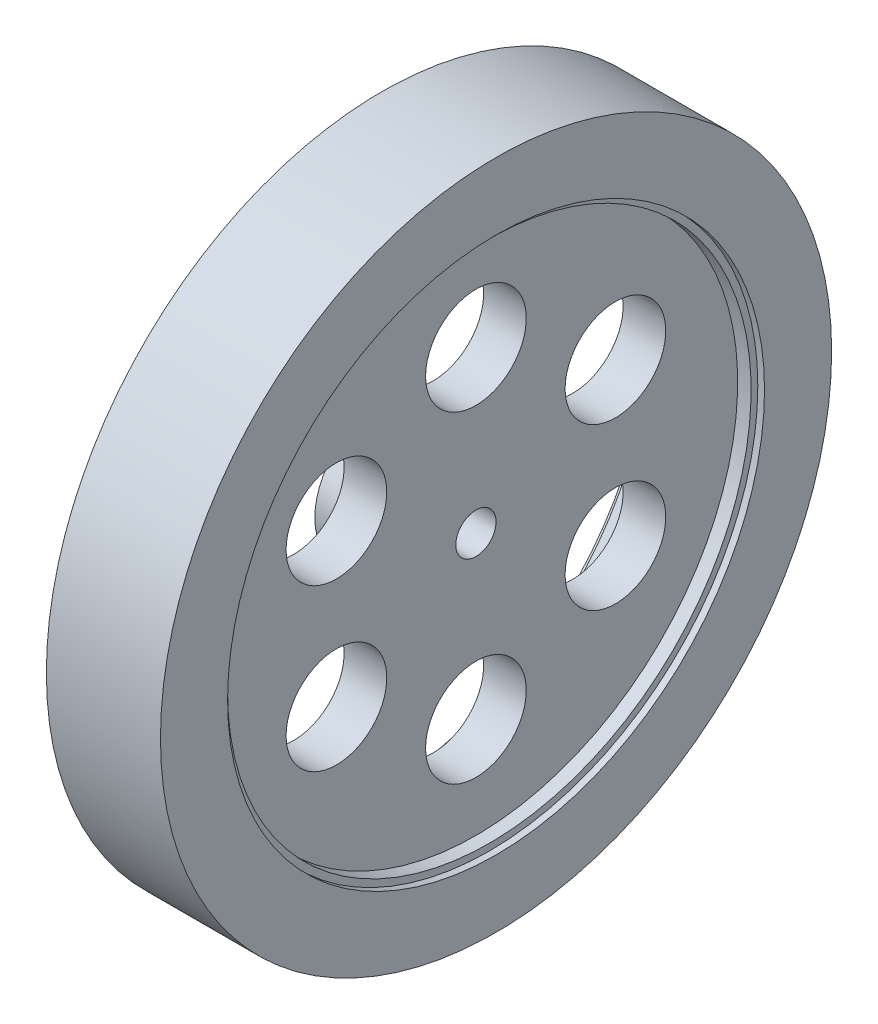
SolidWorks part; units mm, degrees
ref_plane "Front Plane" through (0, 0, 0) normal (0, 0, 1) x (1, 0, 0)
ref_plane "Top Plane" through (0, 0, 0) normal (0, 1, 0) x (1, 0, 0)
ref_plane "Right Plane" through (0, 0, 0) normal (1, 0, 0) x (0, 0, -1)
sketch "Sketch1" plane through (0, 0, 0) normal (0, 0, 1) x (1, 0, 0)
  line L0 (0, 1.5) -> (0, 19.5)
  line L1 (0, 19.5) -> (1, 19.5)
  line L2 (1, 19.5) -> (1, 20)
  line L4 (1.5, 20) -> (1.5, 25)
  line L5 (1.5, 25) -> (-7, 25)
  line L6 (-7, 25) -> (-7, 20)
  line L8 (-3.175, 19.5) -> (-3.175, 5)
  line L9 (-3.175, 0) -> (0, 0) construction
  line L10 (-7, 20) -> (-6.5, 20)
  line L11 (-6.5, 20) -> (-6.5, 19.5)
  line L12 (-6.5, 19.5) -> (-3.175, 19.5)
  line L13 (1, 20) -> (1.5, 20)
  line L14 (-3.175, 1.5) -> (-3.175, 0) construction
  line L15 (-3.175, 1.5) -> (-7, 1.5)
  line L17 (-3.175, 5) -> (-7, 5)
  line L18 (-7, 1.5) -> (-7, 5)
  line L19 (-3.175, 1.5) -> (0, 1.5)
  line L20 (0, 0) -> (0, 1.5) construction
  dimension "D1" = 8.5
  dimension "D2" = 5
  dimension "D3" = 3.175
  dimension "D4" = 0.5
  dimension "D5" = 1
  dimension "D6" = 25
  dimension "D7" = 1.5
  dimension "D8" = 3.5
revolve "Revolve1" add sketch "Sketch1" angle 360 about L9
sketch "Sketch2" plane through (-3.175, 0, 0) normal (-1, 0, 0) x (0, 0, 1)
  line L0 (0, 0) -> (0, 12) construction
  circle A0 centre (0, 12) radius 3.75
  circle A1 centre (10.3923, 6) radius 3.75
  circle A2 centre (10.3923, -6) radius 3.75
  circle A3 centre (0, -12) radius 3.75
  circle A4 centre (-10.3923, -6) radius 3.75
  circle A5 centre (-10.3923, 6) radius 3.75
  point P17 (0, 0)
  dimension "D2" = 7.5
  dimension "D1" = 12
  dimension "D4" = 12
  dimension "D5" = 12
  dimension "D3" = 6
extrude "Cut-Extrude1" cut sketch "Sketch2" against normal blind 10
